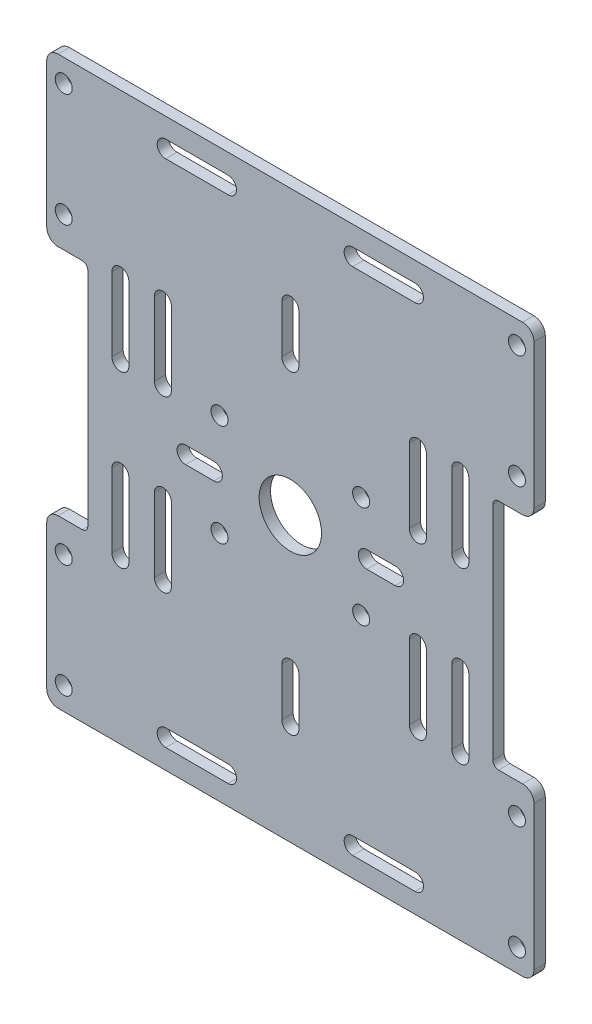
SolidWorks part; units mm, degrees
ref_plane "前基準面" through (0, 0, 0) normal (0, 0, 1) x (1, 0, 0)
ref_plane "上基準面" through (0, 0, 0) normal (0, 1, 0) x (1, 0, 0)
ref_plane "右基準面" through (0, 0, 0) normal (1, 0, 0) x (0, 0, -1)
sketch "草圖1" plane through (0, 0, 0) normal (0, 0, 1) x (1, 0, 0)
  line L0 (-13.5, 0) -> (-18.5, 0) construction
  line L3 (13.5, 0) -> (18.5, 0) construction
  line L4 (13.5, 1.5) -> (18.5, 1.5)
  line L5 (13.5, -1.5) -> (18.5, -1.5)
  line L6 (22.5, -8.5) -> (22.5, -21.5) construction
  line L7 (24, -8.5) -> (24, -21.5)
  line L8 (21, -8.5) -> (21, -21.5)
  line L9 (30, -8.5) -> (30, -21.5) construction
  line L12 (-167.459, 0) -> (250.2577, 0) construction
  line L13 (0, 741.9689) -> (0, -704.7384) construction
  line L14 (31.5, -8.5) -> (31.5, -21.5)
  line L15 (28.5, -8.5) -> (28.5, -21.5)
  line L16 (30, 8.5) -> (30, 21.5) construction
  line L17 (31.5, 8.5) -> (31.5, 21.5)
  line L18 (28.5, 8.5) -> (28.5, 21.5)
  line L19 (22.5, 8.5) -> (22.5, 21.5) construction
  line L20 (24, 8.5) -> (24, 21.5)
  line L21 (21, 8.5) -> (21, 21.5)
  line L22 (-22.5, 8.5) -> (-22.5, 21.5) construction
  line L23 (-24, 8.5) -> (-24, 21.5)
  line L24 (-21, 8.5) -> (-21, 21.5)
  line L25 (-30, 8.5) -> (-30, 21.5) construction
  line L26 (-31.5, 8.5) -> (-31.5, 21.5)
  line L27 (-28.5, 8.5) -> (-28.5, 21.5)
  line L28 (-30, -8.5) -> (-30, -21.5) construction
  line L29 (-31.5, -8.5) -> (-31.5, -21.5)
  line L30 (-28.5, -8.5) -> (-28.5, -21.5)
  line L31 (-22.5, -8.5) -> (-22.5, -21.5) construction
  line L32 (-24, -8.5) -> (-24, -21.5)
  line L33 (-21, -8.5) -> (-21, -21.5)
  line L34 (-22, -45) -> (-11, -45) construction
  line L35 (-22, -43.5) -> (-11, -43.5)
  line L36 (-22, -46.5) -> (-11, -46.5)
  line L37 (22, -45) -> (11, -45) construction
  line L38 (22, -43.5) -> (11, -43.5)
  line L39 (22, -46.5) -> (11, -46.5)
  line L40 (22, 45) -> (11, 45) construction
  line L41 (22, 43.5) -> (11, 43.5)
  line L42 (22, 46.5) -> (11, 46.5)
  line L43 (-22, 45) -> (-11, 45) construction
  line L44 (-22, 43.5) -> (-11, 43.5)
  line L45 (-22, 46.5) -> (-11, 46.5)
  line L46 (-35.75, -20.5625) -> (-43, -20.5625)
  line L47 (-25.75, -50) -> (25.75, -50)
  line L48 (-35.75, -20.5625) -> (-35.75, 20.5625)
  line L49 (-25.75, 50) -> (25.75, 50)
  line L50 (35.75, -20.5625) -> (35.75, 20.5625)
  line L51 (-35.75, -50) -> (35.75, 50) construction
  line L52 (-35.75, 50) -> (35.75, -50) construction
  line L53 (-13.5, 1.5) -> (-18.5, 1.5)
  line L54 (-13.5, -1.5) -> (-18.5, -1.5)
  line L55 (0, -23.5) -> (0, -32) construction
  line L56 (1.5, -23.5) -> (1.5, -32)
  line L57 (-1.5, -23.5) -> (-1.5, -32)
  line L58 (0, 23.5) -> (0, 32) construction
  line L59 (1.5, 23.5) -> (1.5, 32)
  line L60 (-1.5, 23.5) -> (-1.5, 32)
  line L61 (-43, -20.5625) -> (-43, -50)
  line L62 (-43, -50) -> (-25.75, -50)
  line L63 (43, -50) -> (25.75, -50)
  line L64 (43, -20.5625) -> (43, -50)
  line L65 (35.75, -20.5625) -> (43, -20.5625)
  line L66 (35.75, 20.5625) -> (43, 20.5625)
  line L67 (43, 20.5625) -> (43, 50)
  line L68 (43, 50) -> (25.75, 50)
  line L69 (-43, 50) -> (-25.75, 50)
  line L70 (-43, 20.5625) -> (-43, 50)
  line L71 (-35.75, 20.5625) -> (-43, 20.5625)
  circle A0 centre (0, 0) radius 5.5
  circle A4 centre (12.5, -9) radius 1.5
  arc A7 (13.5, 1.5) -> (13.5, -1.5) centre (13.5, 0) ccw
  arc A8 (18.5, -1.5) -> (18.5, 1.5) centre (18.5, 0) ccw
  arc A9 (24, -8.5) -> (21, -8.5) centre (22.5, -8.5) ccw
  arc A10 (21, -21.5) -> (24, -21.5) centre (22.5, -21.5) ccw
  arc A13 (31.5, -8.5) -> (28.5, -8.5) centre (30, -8.5) ccw
  arc A14 (28.5, -21.5) -> (31.5, -21.5) centre (30, -21.5) ccw
  arc A15 (31.5, 8.5) -> (28.5, 8.5) centre (30, 8.5) cw
  arc A16 (28.5, 21.5) -> (31.5, 21.5) centre (30, 21.5) cw
  arc A17 (24, 8.5) -> (21, 8.5) centre (22.5, 8.5) cw
  arc A18 (21, 21.5) -> (24, 21.5) centre (22.5, 21.5) cw
  arc A19 (-24, 8.5) -> (-21, 8.5) centre (-22.5, 8.5) ccw
  arc A20 (-21, 21.5) -> (-24, 21.5) centre (-22.5, 21.5) ccw
  arc A21 (-31.5, 8.5) -> (-28.5, 8.5) centre (-30, 8.5) ccw
  arc A22 (-28.5, 21.5) -> (-31.5, 21.5) centre (-30, 21.5) ccw
  arc A23 (-31.5, -8.5) -> (-28.5, -8.5) centre (-30, -8.5) cw
  arc A24 (-28.5, -21.5) -> (-31.5, -21.5) centre (-30, -21.5) cw
  arc A25 (-24, -8.5) -> (-21, -8.5) centre (-22.5, -8.5) cw
  arc A26 (-21, -21.5) -> (-24, -21.5) centre (-22.5, -21.5) cw
  arc A27 (-22, -43.5) -> (-22, -46.5) centre (-22, -45) ccw
  arc A28 (-11, -46.5) -> (-11, -43.5) centre (-11, -45) ccw
  arc A29 (22, -43.5) -> (22, -46.5) centre (22, -45) cw
  arc A30 (11, -46.5) -> (11, -43.5) centre (11, -45) cw
  arc A31 (22, 43.5) -> (22, 46.5) centre (22, 45) ccw
  arc A32 (11, 46.5) -> (11, 43.5) centre (11, 45) ccw
  arc A33 (-22, 43.5) -> (-22, 46.5) centre (-22, 45) cw
  arc A34 (-11, 46.5) -> (-11, 43.5) centre (-11, 45) cw
  arc A39 (-13.5, 1.5) -> (-13.5, -1.5) centre (-13.5, 0) cw
  arc A40 (-18.5, -1.5) -> (-18.5, 1.5) centre (-18.5, 0) cw
  circle A41 centre (-12.5, -9) radius 1.5
  circle A42 centre (12.5, 9) radius 1.5
  circle A43 centre (-12.5, 9) radius 1.5
  arc A44 (1.5, -23.5) -> (-1.5, -23.5) centre (0, -23.5) ccw
  arc A45 (-1.5, -32) -> (1.5, -32) centre (0, -32) ccw
  arc A46 (1.5, 23.5) -> (-1.5, 23.5) centre (0, 23.5) cw
  arc A47 (-1.5, 32) -> (1.5, 32) centre (0, 32) cw
  circle A48 centre (-40, -26) radius 1.5
  circle A49 centre (40, -26) radius 1.5
  circle A50 centre (40, 26) radius 1.5
  circle A51 centre (-40, 26) radius 1.5
  circle A52 centre (-40, -46) radius 1.5
  circle A53 centre (-40, 46) radius 1.5
  circle A54 centre (40, 46) radius 1.5
  circle A55 centre (40, -46) radius 1.5
  point P5 (0, -27.75)
  point P8 (-16, 0)
  point P18 (16, 0)
  point P25 (22.5, -15)
  point P34 (30, -15)
  point P45 (30, 15)
  point P52 (22.5, 15)
  point P59 (-22.5, 15)
  point P66 (-30, 15)
  point P73 (-30, -15)
  point P80 (-22.5, -15)
  point P87 (-16.5, -45)
  point P94 (16.5, -45)
  point P101 (16.5, 45)
  point P108 (-16.5, 45)
  point P140 (0, 27.75)
  dimension "D2" = 11
  dimension "D3" = 3
  dimension "D4" = 5
  dimension "D6" = 1.5
  dimension "D9" = 23.5
  dimension "D10" = 1.5
  dimension "D11" = 1.5
  dimension "D12" = 1.5
  dimension "D13" = 8.5
  dimension "D20" = 8.5
  dimension "D24" = 1.5
  dimension "D21" = 45
  dimension "D5" = 2.5
  dimension "D25" = 52
  dimension "D27" = 3
  dimension "D28" = 46
  dimension "D29" = 3
  dimension "D7" = 12.5
  dimension "D8" = 9
  dimension "D14" = 60
  dimension "D15" = 7.5
  dimension "D16" = 71.5
  dimension "D17" = 100
  dimension "D18" = 13
  dimension "D19" = 13
  dimension "D22" = 22
  dimension "D23" = 11
  dimension "D26" = 40
  dimension "D30" = 43
extrude "填料-伸長1" add sketch "草圖1" along normal blind 2
fillet "圓角1" radius 1 4 edges at (35.75, -20.5625, 1) (35.75, 20.5625, 1) (-35.75, 20.5625, 1) (-35.75, -20.5625, 1)
fillet "圓角2" radius 2 8 edges at (43, 20.5625, 1) (43, 50, 1) (-43, 50, 1) (-43, 20.5625, 1) (-43, -20.5625, 1) (-43, -50, 1) (43, -50, 1) (43, -20.5625, 1)
